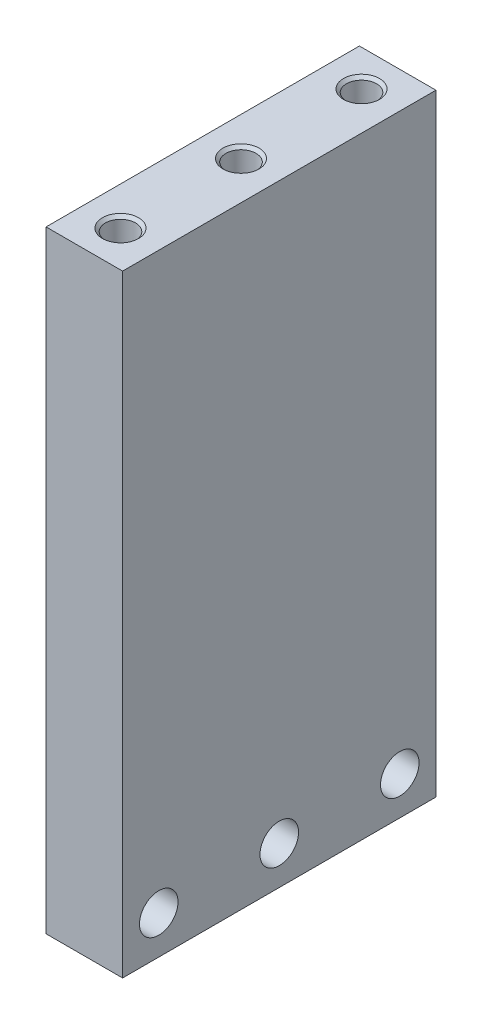
SolidWorks part; units mm, degrees
ref_plane "Front Plane" through (0, 0, 0) normal (0, 0, 1) x (1, 0, 0)
ref_plane "Top Plane" through (0, 0, 0) normal (0, 1, 0) x (1, 0, 0)
ref_plane "Right Plane" through (0, 0, 0) normal (1, 0, 0) x (0, 0, -1)
sketch "Sketch1" plane through (0, 0, 0) normal (0, 0, 1) x (1, 0, 0)
  line L1 (0, 0) -> (6.35, 0)
  line L2 (0, 0) -> (0, 50.8)
  line L3 (0, 50.8) -> (6.35, 50.8)
  line L4 (6.35, 0) -> (6.35, 50.8)
extrude "Boss-Extrude1" add sketch "Sketch1" along normal blind 26
sketch "Sketch4" plane through (6.35, 0, 0) normal (1, 0, 0) x (0, 0, -1)
  line L0 (0, 0) -> (0, 50.8) construction
  line L1 (-26, 0) -> (-26, 50.8) construction
  line L2 (-26, 0) -> (0, 0) construction
  circle A0 centre (-3, 3.175) radius 1.6
  circle A1 centre (-23, 3.175) radius 1.6
  circle A2 centre (-13, 3.175) radius 1.6
  dimension "D1" = 10
  dimension "D2" = 3.2
  dimension "D3" = 3
  dimension "D4" = 3
  dimension "D5" = 3.175
  dimension "D6" = 3.175
extrude "Cut-Extrude3" cut sketch "Sketch4" against normal blind 6.35
sketch "Sketch6" plane through (0, 0, 0) normal (-1, 0, 0) x (0, 0, 1)
  line L0 (26, 0) -> (0, 0) construction
  circle A0 centre (13, 3.175) radius 1.5
  circle A1 centre (3, 3.175) radius 1.6 construction
  dimension "D1" = 3
  dimension "D2" = 10
  dimension "D3" = 3.175
sketch "Sketch9" plane through (0, 50.8, 0) normal (0, 1, 0) x (1, 0, 0)
  line L0 (6.35, 0) -> (0, 0) construction
  line L3 (0, -26) -> (0, 0) construction
  line L4 (0, -11.5) -> (0, -14.5) construction
  circle A6 centre (3.175, -3) radius 1.25
  circle A7 centre (3.175, -13) radius 1.25
  circle A8 centre (3.175, -23) radius 1.25
  dimension "D1" = 3
  dimension "D2" = 10
  dimension "D3" = 10
  dimension "D4" = 20
  dimension "D5" = 3.175
  dimension "D6" = 3.175
sketch "Sketch12" plane through (0, 50.8, 0) normal (0, 1, 0) x (1, 0, 0)
  circle A0 centre (3.175, -3) radius 1.25
  circle A1 centre (3.175, -13) radius 1.25
  circle A2 centre (3.175, -23) radius 1.25
  dimension "D1" = 2.5
  dimension "D2" = 2.5
  dimension "D3" = 2.5
sketch "Sketch14" plane through (0, 50.8, 0) normal (0, 1, 0) x (1, 0, 0)
  circle A0 centre (3.175, -23) radius 1.25 construction
  circle A1 centre (3.175, -13) radius 1.25 construction
  circle A2 centre (3.175, -3) radius 1.25 construction
  circle A3 centre (3.175, -23) radius 1.25
  circle A4 centre (3.175, -13) radius 1.25
  circle A5 centre (3.175, -3) radius 1.25
extrude "Cut-Extrude13" cut sketch "Sketch14" against normal blind 5
chamfer "Chamfer3" distance 0.25 angle 45 3 edges at (3.175, 50.8, 24.25) (3.175, 50.8, 14.25) (3.175, 50.8, 4.25)
